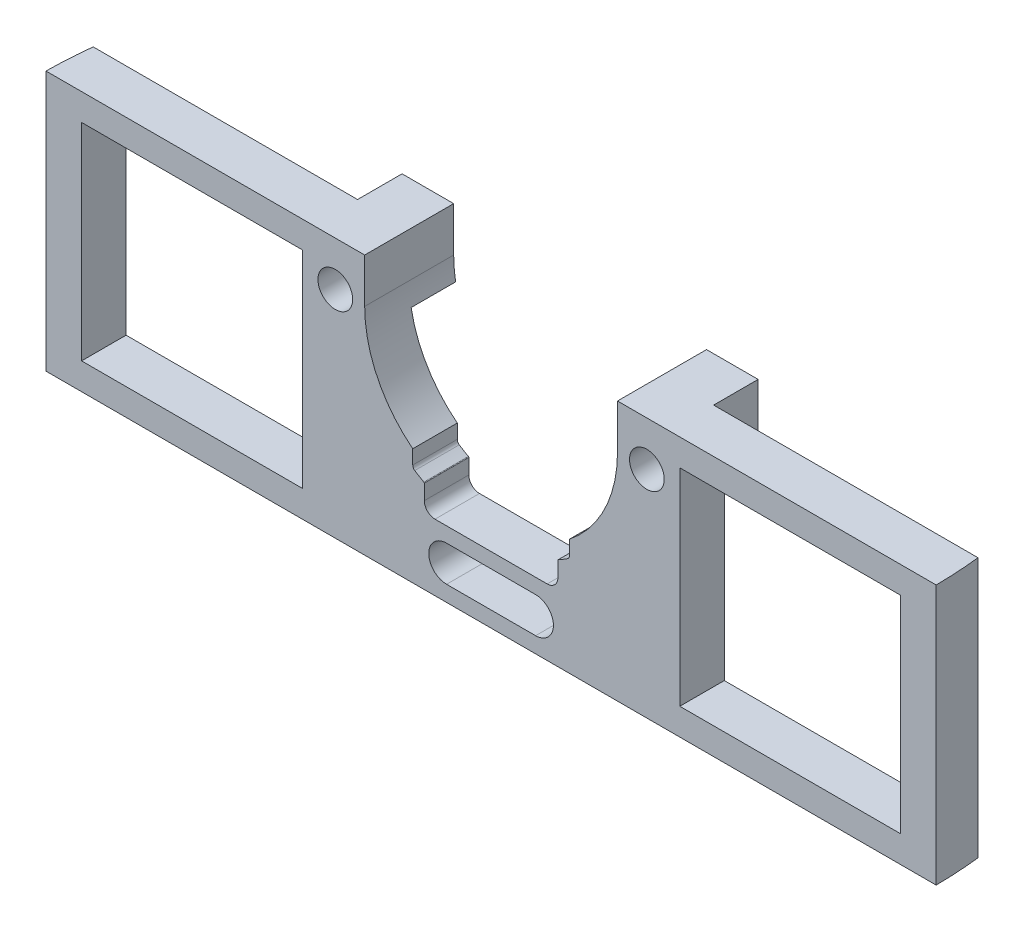
SolidWorks part; units mm, degrees
ref_plane "Front Plane" through (0, 0, 0) normal (0, 0, 1) x (1, 0, 0)
ref_plane "Top Plane" through (0, 0, 0) normal (0, 1, 0) x (1, 0, 0)
ref_plane "Right Plane" through (0, 0, 0) normal (1, 0, 0) x (0, 0, -1)
sketch "Sketch1" plane through (0, 0, 0) normal (0, 0, 1) x (1, 0, 0)
  line L0 (14.2, 0) -> (14.2, 5)
  line L1 (14.2, 5) -> (50, 5)
  line L2 (0, 14.2) -> (10.4714, 14.2) construction
  line L3 (0, -12.8109) -> (0, -28.0522) construction
  line L4 (50, 5) -> (50, -24.2)
  line L6 (50, -24.2) -> (-50, -24.2)
  line L8 (-50, 5) -> (-50, -24.2)
  line L9 (-14.2, 5) -> (-50, 5)
  line L10 (-14.2, 0) -> (-14.2, 5)
  line L11 (-5, -20.4316) -> (5, -20.4316) construction
  line L12 (-5, -18.4316) -> (5, -18.4316)
  line L13 (-5, -22.4316) -> (5, -22.4316)
  arc A0 (-14.2, 0) -> (14.2, 0) centre (0, 0) ccw
  arc A1 (-5, -18.4316) -> (-5, -22.4316) centre (-5, -20.4316) ccw
  arc A2 (5, -22.4316) -> (5, -18.4316) centre (5, -20.4316) ccw
  point P9 (0, -24.2)
  point P17 (0, -20.4316)
  point P22 (0, 0)
  dimension "D1" = 28.4
  dimension "D5" = 10
  dimension "D2" = 5
  dimension "D3" = 50
  dimension "D4" = 10
  dimension "D6" = 4
extrude "Boss-Extrude1" add sketch "Sketch1" along normal blind 5
sketch "Sketch2" plane through (0, 0, 5) normal (0, 0, 1) x (1, 0, 0)
  line L0 (-50, 5) -> (-50, -24.2) construction
  line L1 (-46, 2) -> (-21.2, 2)
  line L2 (-46, 2) -> (-46, -21.2)
  line L3 (-46, -21.2) -> (-21.2, -21.2)
  line L4 (-21.2, 2) -> (-21.2, -21.2)
  line L5 (-14.2, 5) -> (-50, 5) construction
  line L6 (-50, -24.2) -> (50, -24.2) construction
  line L7 (-14.2, 0) -> (-14.2, 5) construction
  line L8 (0, 0) -> (0, 8.2099) construction
  line L9 (46, -21.2) -> (21.2, -21.2)
  line L10 (21.2, 2) -> (21.2, -21.2)
  line L11 (46, 2) -> (21.2, 2)
  line L12 (46, 2) -> (46, -21.2)
  dimension "D1" = 4
  dimension "D2" = 3
  dimension "D3" = 3
  dimension "D4" = 7
extrude "Cut-Extrude1" cut sketch "Sketch2" against normal up to surface (5 mm away) up to face at (0, -5.325, 0)
sketch "Sketch3" plane through (0, 0, 0) normal (0, 0, -1) x (-1, 0, 0)
  line L0 (-20, 0) -> (-20, 5)
  line L2 (-50, 5) -> (-14.2, 5) construction
  line L3 (-17.5, -2.5) -> (-13.9782, -2.5)
  line L4 (-14.2, 5) -> (-14.2, 0) construction
  line L5 (-20, 5) -> (-14.2, 5)
  line L6 (-14.2, 5) -> (-14.2, 0)
  line L7 (0, 0) -> (0, 5.6372) construction
  line L8 (20, 5) -> (14.2, 5)
  line L9 (20, 0) -> (20, 5)
  line L10 (17.5, -2.5) -> (13.9782, -2.5)
  line L11 (14.2, 5) -> (14.2, 0)
  arc A3 (-20, 0) -> (-17.5, -2.5) centre (-17.5, 0) ccw
  circle A4 centre (-17.5, 0) radius 2.05 construction
  arc A5 (-14.2, 0) -> (14.2, 0) centre (0, 0) ccw construction
  arc A6 (-14.2, 0) -> (-13.9782, -2.5) centre (0, 0) ccw
  circle A7 centre (17.5, 0) radius 2.05 construction
  arc A8 (20, 0) -> (17.5, -2.5) centre (17.5, 0) cw
  arc A9 (14.2, 0) -> (13.9782, -2.5) centre (0, 0) cw
  arc M9 (14.2, 0) -> (-14.2, 0) centre (0, 0) cw
  line M10 (-14.2, 0) -> (-14.2, 5)
  line M11 (-14.2, 5) -> (-50, 5)
  line M15 (50, 5) -> (14.2, 5)
  line M16 (14.2, 5) -> (14.2, 0)
  dimension "D1" = 5
extrude "Boss-Extrude2" add sketch "Sketch3" along normal blind 5 contours L0 A3 L3 M9 M10 M11 | A8 L9 L10 M15 M16 M9
sketch "Sketch4" plane through (0, 0, -5) normal (0, 0, -1) x (-1, 0, 0)
  circle A0 centre (-17.5, 0) radius 1.95
  circle A1 centre (17.5, 0) radius 1.95
  dimension "D1" = 3.9
  dimension "D2" = 3.9
extrude "Cut-Extrude2" cut sketch "Sketch4" against normal up to surface (10 mm away) up to face at (-33.6, -9.6, 5)
sketch "Sketch5" plane through (0, 0, 5) normal (0, 0, 1) x (1, 0, 0)
  line L3 (-7.3, -15.5472) -> (-7.3, -13.8521) construction
  line L4 (6.3, -16.5472) -> (-6.3, -16.5472) construction
  line L5 (7.3, -13.8521) -> (7.3, -15.5472) construction
  line L6 (-8.6, -12.7338) -> (-8.6, -11.2996) construction
  line L7 (8.6, -12.7338) -> (8.6, -11.2996) construction
  line L8 (-8.6, -11.2996) -> (8.6, -11.2996) construction
  line L9 (-7.5, -15.5472) -> (-7.5, -13.8521)
  line L10 (-8.8, -12.7338) -> (-8.8, -11.0996)
  line L11 (-8.8, -11.0996) -> (8.8, -11.0996)
  line L12 (8.8, -12.7338) -> (8.8, -11.0996)
  line L13 (7.5, -13.8521) -> (7.5, -15.5472)
  line L14 (6.3, -16.7472) -> (-6.3, -16.7472)
  arc A8 (-8.6, -12.7338) -> (-8.4638, -12.9851) centre (-8.3, -12.7338) ccw construction
  arc A9 (-8.4638, -12.9851) -> (-7.4557, -13.5891) centre (0, 0) ccw construction
  arc A10 (-7.3, -13.8521) -> (-7.4557, -13.5891) centre (-7.6, -13.8521) ccw construction
  arc A11 (-7.3, -15.5472) -> (-6.3, -16.5472) centre (-6.3, -15.5472) ccw construction
  arc A12 (6.3, -16.5472) -> (7.3, -15.5472) centre (6.3, -15.5472) ccw construction
  arc A13 (7.4557, -13.5891) -> (7.3, -13.8521) centre (7.6, -13.8521) ccw construction
  arc A14 (8.4638, -12.9851) -> (8.6, -12.7338) centre (8.3, -12.7338) ccw construction
  arc A15 (7.4557, -13.5891) -> (8.4638, -12.9851) centre (0, 0) ccw construction
  arc A16 (-14.2, 0) -> (14.2, 0) centre (0, 0) ccw construction
  arc A17 (-7.5, -13.8521) -> (-7.5519, -13.7644) centre (-7.6, -13.8521) ccw
  arc A18 (-8.573, -13.1527) -> (-7.5519, -13.7644) centre (0, 0) ccw
  arc A19 (-8.8, -12.7338) -> (-8.573, -13.1527) centre (-8.3, -12.7338) ccw
  arc A20 (8.573, -13.1527) -> (8.8, -12.7338) centre (8.3, -12.7338) ccw
  arc A21 (7.5519, -13.7644) -> (8.573, -13.1527) centre (0, 0) ccw
  arc A22 (7.5519, -13.7644) -> (7.5, -13.8521) centre (7.6, -13.8521) ccw
  arc A23 (6.3, -16.7472) -> (7.5, -15.5472) centre (6.3, -15.5472) ccw
  arc A24 (-7.5, -15.5472) -> (-6.3, -16.7472) centre (-6.3, -15.5472) ccw
  dimension "D1" = 0.2
extrude "Cut-Extrude3" cut sketch "Sketch5" against normal up to surface (5 mm away) up to face at (0, -20.4316, 0)
sketch "Sketch7" plane through (0, 5, 0) normal (0, 1, 0) x (1, 0, 0)
  line L0 (49.6966, 0) -> (50, 0)
  line L2 (50, 0) -> (50, -5)
  line L3 (50, -5) -> (49.998, -5.0499)
  line L5 (0, -5.5) -> (0, -0.8718) construction
  line L6 (-50, -5) -> (-49.998, -5.0499)
  line L7 (-50, 0) -> (-50, -5)
  line L8 (-49.6966, 0) -> (-50, 0)
  arc A0 (49.998, -5.0499) -> (49.6966, 0) centre (0, -5.5) ccw
  arc A1 (-49.998, -5.0499) -> (-49.6966, 0) centre (0, -5.5) cw
  dimension "D1" = 100
extrude "Cut-Extrude4" cut sketch "Sketch7" against normal up to surface (29.2 mm away) up to face at (0, -24.2, 2.5)
